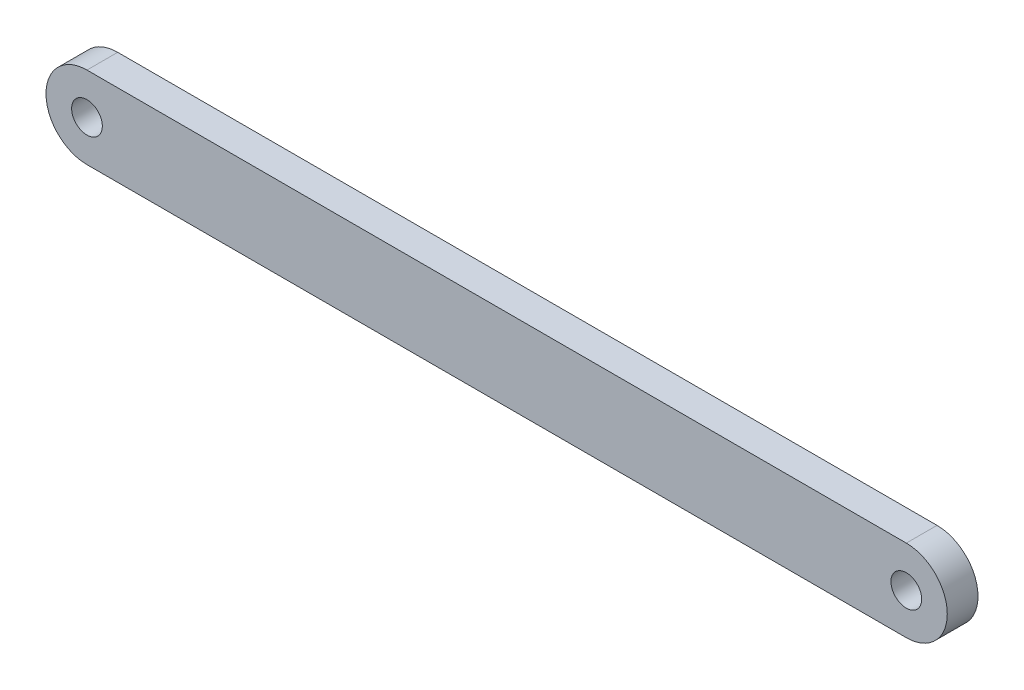
SolidWorks part; units mm, degrees
material "Acrílico (médio-alto impacto)"
ref_plane "Plano frontal" through (0, 0, 0) normal (0, 0, 1) x (1, 0, 0)
ref_plane "Plano superior" through (0, 0, 0) normal (0, 1, 0) x (1, 0, 0)
ref_plane "Plano direito" through (0, 0, 0) normal (1, 0, 0) x (0, 0, -1)
sketch "Esboço1" plane through (0, 0, 0) normal (0, 0, 1) x (1, 0, 0)
  line L0 (-40, 0) -> (40, 0) construction
  line L1 (-40, 4) -> (40, 4)
  line L2 (-40, -4) -> (40, -4)
  arc A0 (-40, 4) -> (-40, -4) centre (-40, 0) ccw
  arc A1 (40, -4) -> (40, 4) centre (40, 0) ccw
  point P2 (0, 0)
  dimension "D3" = 88
  dimension "D1" = 80
  dimension "D2" = 8
extrude "Ressalto-extrusão1" add sketch "Esboço1" along normal blind 3
hole_wizard "Furo de diâmetro Ø3.0 (3)1" positions "Esboço2" profile "Esboço3" hole size "Ø3.0" standard "ISO" end condition through all
sketch "Esboço2" plane through (0, 0, 3) normal (0, 0, 1) x (1, 0, 0)
  point P0 (-40, 0)
  point P3 (40, 0)
sketch "Esboço3" plane through (-40, 0, 3) normal (1, 0, 0) x (0, -1, 0)
  line L0 (0, 0) -> (0, 3)
  line L1 (0, 3) -> (1.5, 3)
  line L2 (1.5, 3) -> (1.5, 0)
  line L5 (1.5, 0) -> (0, 0)
  line L11 (0, -6.35) -> (0, 107.95) construction
  dimension "Thru Hole Dia." = 3
  dimension "Thru Hole Depth" = 3
